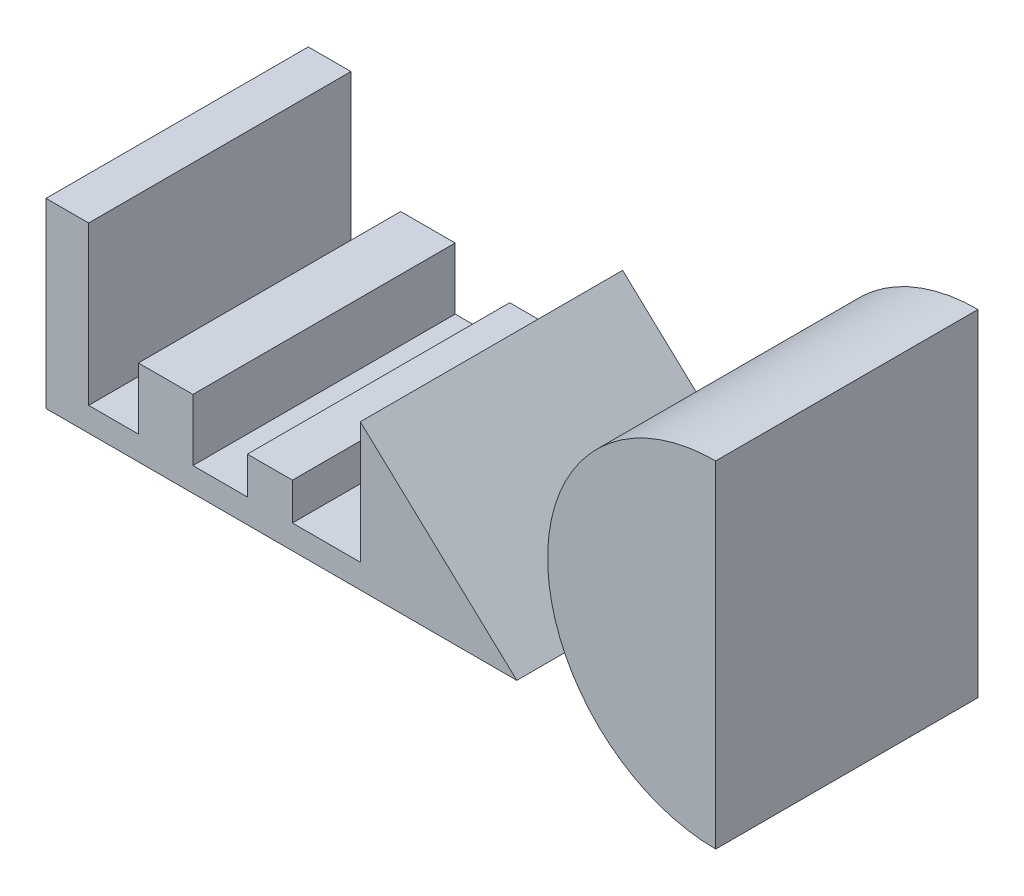
SolidWorks part; units mm, degrees
ref_plane "Front Plane" through (0, 0, 0) normal (0, 0, 1) x (1, 0, 0)
ref_plane "Top Plane" through (0, 0, 0) normal (0, 1, 0) x (1, 0, 0)
ref_plane "Right Plane" through (0, 0, 0) normal (1, 0, 0) x (0, 0, -1)
sketch "Sketch1" plane through (0, 0, 0) normal (0, 0, 1) x (1, 0, 0)
  line L0 (0, 0) -> (0, 264.4383)
  line L1 (0, 264.4383) -> (61.9508, 264.4383)
  line L2 (61.9508, 264.4383) -> (61.9508, 34.9907)
  line L3 (61.9508, 34.9907) -> (134.2268, 34.9907)
  line L4 (134.2268, 34.9907) -> (134.2268, 124.4753)
  line L5 (134.2268, 124.4753) -> (213.3862, 124.4753)
  line L6 (213.3862, 124.4753) -> (213.3862, 34.9907)
  line L7 (213.3862, 34.9907) -> (292.5456, 34.9907)
  line L8 (292.5456, 34.9907) -> (292.5456, 88.9109)
  line L9 (292.5456, 88.9109) -> (357.9381, 88.9109)
  line L10 (357.9381, 88.9109) -> (357.9381, 34.9907)
  line L11 (357.9381, 34.9907) -> (456.6006, 34.9907)
  line L12 (456.6006, 34.9907) -> (456.6006, 211.6653)
  line L13 (456.6006, 211.6653) -> (683.9372, 0)
  line L14 (683.9372, 0) -> (0, 0)
  line L15 (972.8798, 420.6031) -> (972.8798, -67.7629)
  arc A0 (972.8798, 420.6031) -> (972.8798, -67.7629) centre (972.8798, 176.4201) ccw
extrude "Boss-Extrude1" add sketch "Sketch1" along normal mid plane 381
